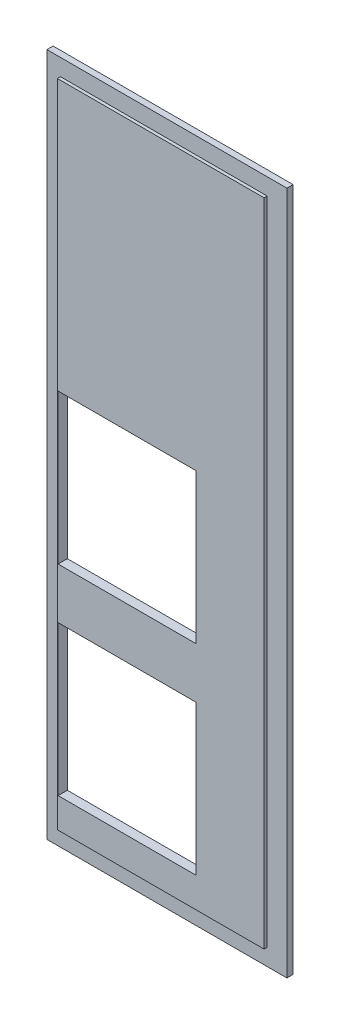
SolidWorks part; units mm, degrees
ref_plane "Спереди" through (0, 0, 0) normal (0, 0, 1) x (1, 0, 0)
ref_plane "Сверху" through (0, 0, 0) normal (0, 1, 0) x (1, 0, 0)
ref_plane "Справа" through (0, 0, 0) normal (1, 0, 0) x (0, 0, -1)
ref_plane "Плоскость4" through (0.5, 0, 0) normal (-1, 0, 0) x (0, -1, 0)
sketch "Эскиз1" plane through (0.5, 0, 0) normal (0, 0, 1) x (0, -1, 0)
  line L0 (9.85, 42.25) -> (-100.85, 42.25)
  line L1 (-100.85, 42.25) -> (-100.85, 3.4)
  line L2 (-100.85, 3.4) -> (9.85, 3.4)
  line L3 (9.85, 3.4) -> (9.85, 42.25)
extrude "Бобышка-Вытянуть1" add sketch "Эскиз1" against normal blind 1
sketch "Эскиз2" plane through (0, 0, 0) normal (0, 0, 1) x (1, 0, 0)
  line L0 (39.55, -7.15) -> (6.1, -7.15)
  line L1 (6.1, -7.15) -> (6.1, 98.15)
  line L2 (6.1, 98.15) -> (39.55, 98.15)
  line L3 (39.55, 98.15) -> (39.55, -7.15)
extrude "Бобышка-Вытянуть2" add sketch "Эскиз2" along normal blind 0.5
sketch "Эскиз3" plane through (0, 0, 0.5) normal (0, 0, 1) x (1, 0, 0)
  line L1 (6.2162, 54.4) -> (28.5556, 54.4)
  line L2 (6.2162, 54.4) -> (6.2162, 30.15)
  line L3 (6.2162, 30.15) -> (28.5556, 30.15)
  line L4 (28.5556, 54.4) -> (28.5556, 30.15)
  line L5 (6.2162, 21.9444) -> (28.5556, 21.9444)
  line L6 (6.2162, 21.9444) -> (6.2162, -2.3056)
  line L7 (6.2162, -2.3056) -> (28.5556, -2.3056)
  line L8 (28.5556, 21.9444) -> (28.5556, -2.3056)
extrude "Вырез-Вытянуть1" cut sketch "Эскиз3" against normal blind 2
